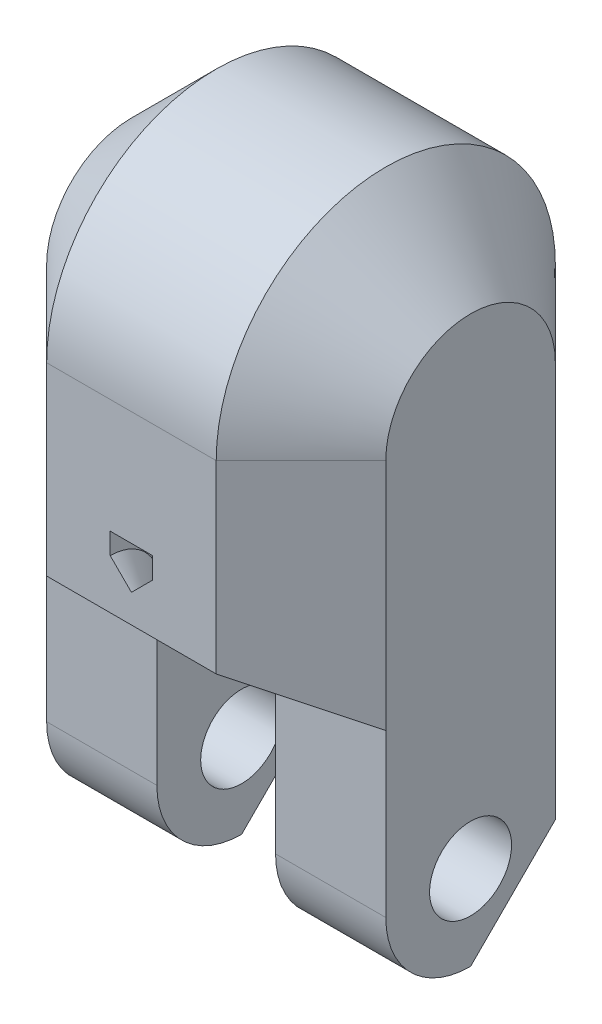
SolidWorks part; units mm, degrees
ref_plane "Front Plane" through (0, 0, 0) normal (0, 0, 1) x (1, 0, 0)
ref_plane "Top Plane" through (0, 0, 0) normal (0, 1, 0) x (1, 0, 0)
ref_plane "Right Plane" through (0, 0, 0) normal (1, 0, 0) x (0, 0, -1)
sketch "Sketch2" plane through (0, 0, 0) normal (0, 1, 0) x (1, 0, 0)
  line L0 (-3, 6) -> (3, 6)
  line L1 (3, 6) -> (6, 3)
  line L2 (6, 3) -> (6, -3)
  line L3 (6, -3) -> (3, -6)
  line L4 (3, -6) -> (-3, -6)
  line L5 (-3, -6) -> (-6, -3)
  line L6 (-6, -3) -> (-6, 3)
  line L7 (-6, 3) -> (-3, 6)
  point P2 (0, -6)
  point P9 (0, 6)
  point P12 (-6, 0)
  point P13 (6, 0)
  dimension "D1" = 12
  dimension "D2" = 12
  dimension "D3" = 6
  dimension "D4" = 6
  dimension "D5" = 6
extrude "Boss-Extrude1" add sketch "Sketch2" along normal mid plane 10 contours L7 L0 L1 L2 L3 L4 L5 L6
sketch "Sketch22" plane through (0, 0, 0) normal (1, 0, 0) x (0, 0, -1)
  line L0 (0, -5) -> (-6, -5)
  line L1 (3, -5) -> (-3, -5) construction
  line L2 (-6, -5) -> (-6, -1.5359)
  line L3 (-6, 5) -> (-6, -5) construction
  line L4 (-6, -1.5359) -> (0, -5)
  dimension "D1" = 30
extrude "Cut-Extrude8" cut sketch "Sketch22" against normal through all both and the other way through all
sketch "Sketch23" plane through (0, 5, 0) normal (0, 1, 0) x (1, 0, 0)
  line L0 (-6, 0) -> (-6, 3)
  line L1 (-6, -3) -> (-6, 3) construction
  line L2 (-6, 3) -> (-3, 6)
  line L3 (-3, 6) -> (3, 6)
  line L4 (3, 6) -> (6, 3)
  line L5 (6, 3) -> (6, 0)
  line L6 (6, 3) -> (6, -3) construction
  line L7 (6, 0) -> (-6, 0)
revolve "Revolve1" add sketch "Sketch23" angle 180 about L7
sketch "Sketch24" plane through (0, -5, 0) normal (0, -1, 0) x (1, 0, 0)
  line L1 (-6, -3) -> (-2.1, -3)
  line L2 (-6, -3) -> (-6, 3)
  line L3 (-6, 3) -> (-2.1, 3)
  line L4 (-2.1, -3) -> (-2.1, 3)
  dimension "D1" = 3.9
extrude "Boss-Extrude2" add sketch "Sketch24" along normal mid plane 8
sketch "Sketch25" plane through (0, -9, 0) normal (0, -1, 0) x (1, 0, 0)
  line L0 (-6, 3) -> (-6, -3) construction
  line L2 (-6, 0) -> (-6, 3)
  line L3 (-6, 3) -> (-2.1, 3)
  line L4 (-2.1, 0) -> (-2.1, 3)
  line L5 (-6, 0) -> (-2.1, 0)
revolve "Revolve2" add sketch "Sketch25" angle 180 about L5
sketch "Sketch26" plane through (-6, 0, 0) normal (-1, 0, 0) x (0, 0, 1)
  line L0 (-3, -9) -> (3, -9) construction
  circle A0 centre (0, -9) radius 1.45
  dimension "D1" = 2.9
extrude "Cut-Extrude9" cut sketch "Sketch26" against normal through all both and the other way through all
mirror "Mirror1" about plane through (0, 0, 0) normal (1, 0, 0) of "Revolve2", "Cut-Extrude9", "Boss-Extrude2"
sketch "Sketch30" plane through (0, -3.75, 2.1651) normal (0, -0.866, 0.5) x (1, 0, 0)
  line L0 (0, 3.4282) -> (-0.75, 2.6782)
  line L1 (-0.75, 2.6782) -> (-0.75, 1.9282)
  line L2 (-0.75, 1.9282) -> (0.75, 1.9282)
  line L3 (0.75, 1.9282) -> (0.75, 2.6782)
  line L4 (0.75, 2.6782) -> (0, 3.4282)
  line L5 (-3, 4.4282) -> (3, 4.4282) construction
  point P10 (0, 4.4282)
  dimension "D1" = 135
  dimension "D2" = 0.75
  dimension "D3" = 1.5
  dimension "D4" = 1
revolve "Cut-Revolve1" cut sketch "Sketch30" angle 360 about axis through (-6, -1.5359, 6) along (1, 0, 0)
sketch "Sketch34" plane through (0, -5, 0) normal (0, -1, 0) x (1, 0, 0)
  line L0 (-6, -3) -> (-2.1, -3)
  line L1 (-2.1, -3) -> (2.1, -3)
  line L2 (2.1, -3) -> (6, -3)
  line L3 (6, -3) -> (3, -6)
  line L4 (3, -6) -> (-3, -6)
  line L5 (-3, -6) -> (-6, -3)
extrude "Boss-Extrude4" add sketch "Sketch34" along normal blind 3.7
sketch "Sketch35" plane through (0, -8.7, 0) normal (0, -1, 0) x (1, 0, 0)
  line L0 (0, -3.5) -> (-0.75, -4.25)
  line L1 (-0.75, -4.25) -> (-0.75, -5)
  line L2 (-0.75, -5) -> (0.75, -5)
  line L3 (0.75, -5) -> (0.75, -4.25)
  line L4 (0.75, -4.25) -> (0, -3.5)
  line L5 (-3, -6) -> (3, -6) construction
  dimension "D1" = 1.5
  dimension "D2" = 1.5
  dimension "D3" = 1
  dimension "D4" = 135
revolve "Cut-Revolve3" cut sketch "Sketch35" angle 360 about axis through (3, -8.7, -6) along (1, 0, 0)
sketch "Sketch36" plane through (-6, 0, 0) normal (-1, 0, 0) x (0, 0, 1)
  line L0 (-3, -9) -> (0, -12)
  line L1 (0, -12) -> (0, -13.5285)
  line L2 (0, -13.5285) -> (-3.6434, -13.5285)
  line L3 (-3.6434, -13.5285) -> (-3.6434, -9)
  line L4 (-3.6434, -9) -> (-3, -9)
  arc A0 (-3, -9) -> (3, -9) centre (0, -9) ccw construction
extrude "Cut-Extrude10" cut sketch "Sketch36" against normal through all both and the other way through all
